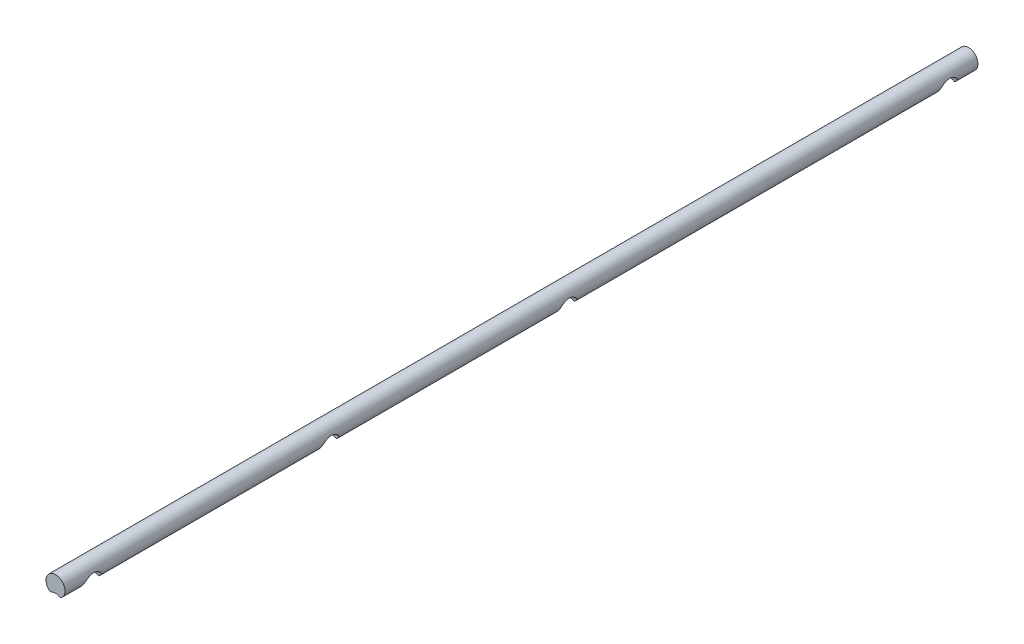
SolidWorks part; units mm, degrees
ref_plane "Спереди" through (0, 0, 0) normal (0, 0, 1) x (1, 0, 0)
ref_plane "Сверху" through (0, 0, 0) normal (0, 1, 0) x (1, 0, 0)
ref_plane "Справа" through (0, 0, 0) normal (1, 0, 0) x (0, 0, -1)
sketch "Эскиз1" plane through (0, 0, 0) normal (0, 0, 1) x (1, 0, 0)
  line L0 (0, 100) -> (0, -70) construction
  circle A0 centre (0, 0) radius 100
  circle A2 centre (0, -175) radius 105
  point P6 (0, 0)
  dimension "D1" = 200
  dimension "D3" = 210
  dimension "D2" = 170
extrude "Бобышка-Вытянуть1" add sketch "Эскиз1" along normal mid plane 9600 contours A0 L0 A2 | L0 A0 A2
sketch "Эскиз2" plane through (0, 0, 0) normal (1, 0, 0) x (0, 0, -1)
  line L0 (-4800, 100) -> (-4800, -84.5714) construction
  line L1 (-4800, -84.5714) -> (4800, -84.5714) construction
  line L2 (0, 0) -> (0, 114.413) construction
  circle A0 centre (-4500, -84.5714) radius 100
  circle A1 centre (4500, -84.5714) radius 100
  circle A2 centre (-2000, -84.5714) radius 100
  circle A3 centre (500, -84.5714) radius 100
  dimension "D2" = 200
  dimension "D1" = 300
  dimension "D3" = 2500
  dimension "D4" = 2500
extrude "Вырез-Вытянуть1" cut sketch "Эскиз2" against normal mid plane 6000
sketch "Эскиз3" plane through (0, 0, 0) normal (0, 1, 0) x (1, 0, 0)
  line L0 (-100, -4800) -> (100, -4800) construction
  line L1 (0, -4420.923) -> (0, -4579.077) construction
  line L2 (-79.077, -4500) -> (79.077, -4500) construction
  line L3 (0, 0) -> (163.9977, 0) construction
  line L4 (-79.077, 4500) -> (79.077, 4500) construction
  line L5 (0, 4420.923) -> (0, 4579.077) construction
  line L6 (0, -1920.923) -> (0, -2079.077) construction
  line L7 (-79.077, -2000) -> (79.077, -2000) construction
  line L8 (0, 579.077) -> (0, 420.923) construction
  line L9 (-79.077, 500) -> (79.077, 500) construction
  circle A0 centre (0, -4500) radius 79.077 construction
  circle A1 centre (0, 4500) radius 79.077 construction
  circle A2 centre (0, -2000) radius 79.077 construction
  circle A3 centre (0, 500) radius 79.077 construction
  dimension "D2" = 158.1541
  dimension "D1" = 300
  dimension "D3" = 2500
  dimension "D4" = 2500
equation "\"Длина\"= 9600"
equation "\"D1@Бобышка-Вытянуть1\"=\"Длина\""
